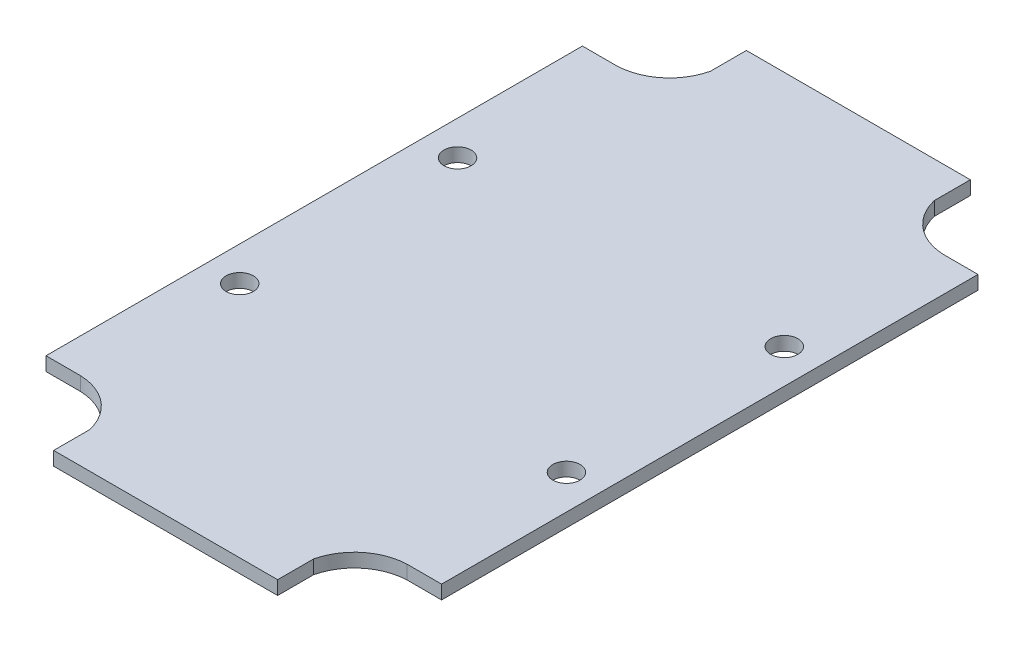
SolidWorks part; units mm, degrees
ref_plane "Front Plane" through (0, 0, 0) normal (0, 0, 1) x (1, 0, 0)
ref_plane "Top Plane" through (0, 0, 0) normal (0, 1, 0) x (1, 0, 0)
ref_plane "Right Plane" through (0, 0, 0) normal (1, 0, 0) x (0, 0, -1)
sketch "Sketch1" plane through (0, 0, 0) normal (0, 1, 0) x (1, 0, 0)
  line L0 (-23.0632, 31.274) -> (-19.05, 31.274)
  line L1 (-23.0632, -40.386) -> (23.0632, -40.386) construction
  line L2 (-23.0632, -40.386) -> (-23.0632, 40.386) construction
  line L3 (-23.0632, 40.386) -> (23.0632, 40.386) construction
  line L4 (23.0632, -40.386) -> (23.0632, 40.386) construction
  line L5 (0, 40.386) -> (0, -40.386) construction
  line L6 (-23.0632, 0) -> (23.0632, 0) construction
  line L7 (-13.0557, 36.195) -> (-13.0557, 40.386)
  line L8 (13.0557, 36.195) -> (13.0557, 40.386)
  line L9 (23.0632, 31.274) -> (19.05, 31.274)
  line L10 (23.0632, -31.274) -> (19.05, -31.274)
  line L11 (13.0557, -36.195) -> (13.0557, -40.386)
  line L12 (-13.0557, -36.195) -> (-13.0557, -40.386)
  line L13 (-23.0632, -31.274) -> (-19.05, -31.274)
  line L14 (-13.0557, -40.386) -> (13.0557, -40.386)
  line L15 (-23.0632, -31.274) -> (-23.0632, 0)
  line L16 (-23.0632, 0) -> (-23.0632, 31.274)
  line L17 (-13.0557, 40.386) -> (13.0557, 40.386)
  line L18 (23.0632, 31.274) -> (23.0632, -31.274)
  arc A0 (-13.0557, 36.195) -> (-19.05, 31.274) centre (-19.2435, 37.621) cw
  arc A1 (13.0557, 36.195) -> (19.05, 31.274) centre (19.2435, 37.621) ccw
  arc A2 (13.0557, -36.195) -> (19.05, -31.274) centre (19.2435, -37.621) cw
  arc A3 (-13.0557, -36.195) -> (-19.05, -31.274) centre (-19.2435, -37.621) ccw
  point P0 (0, 0)
  dimension "D3" = 6.35
  dimension "D4" = 4.0132
  dimension "D5" = 4.191
  dimension "D6" = 9.112
  dimension "D1" = 80.772
  dimension "D2" = 46.1264
  dimension "D7" = 10.0075
extrude "Boss-Extrude1" add sketch "Sketch1" along normal blind 1.6
sketch "Sketch2" plane through (0, 1.6, 0) normal (0, 1, 0) x (1, 0, 0)
  line L0 (0, 0) -> (50000, 0) construction
  line L1 (23.0632, -31.274) -> (23.0632, 31.274) construction
  line L2 (0, 0) -> (0, 50000) construction
  line L3 (0, -12.7) -> (0, 12.7) construction
  line L4 (-19.05, 0) -> (19.05, 0) construction
  line L7 (-23.0632, 31.274) -> (-23.0632, -31.274) construction
  line L8 (-19.05, 0) -> (-19.05, 12.7) construction
  line L9 (19.05, 0) -> (19.05, 12.7) construction
  circle A0 centre (-19.05, 12.7) radius 1.5875
  circle A1 centre (19.05, 12.7) radius 1.5875
  circle A2 centre (19.05, -12.7) radius 1.5875
  circle A3 centre (-19.05, -12.7) radius 1.5875
  point P5 (23.0632, 0)
  dimension "D7" = 3.175
  dimension "D1" = 25.4
  dimension "D2" = 12.7
  dimension "D4" = 4.0132
  dimension "D5" = 12.7
extrude "Cut-Extrude1" cut sketch "Sketch2" against normal through all
